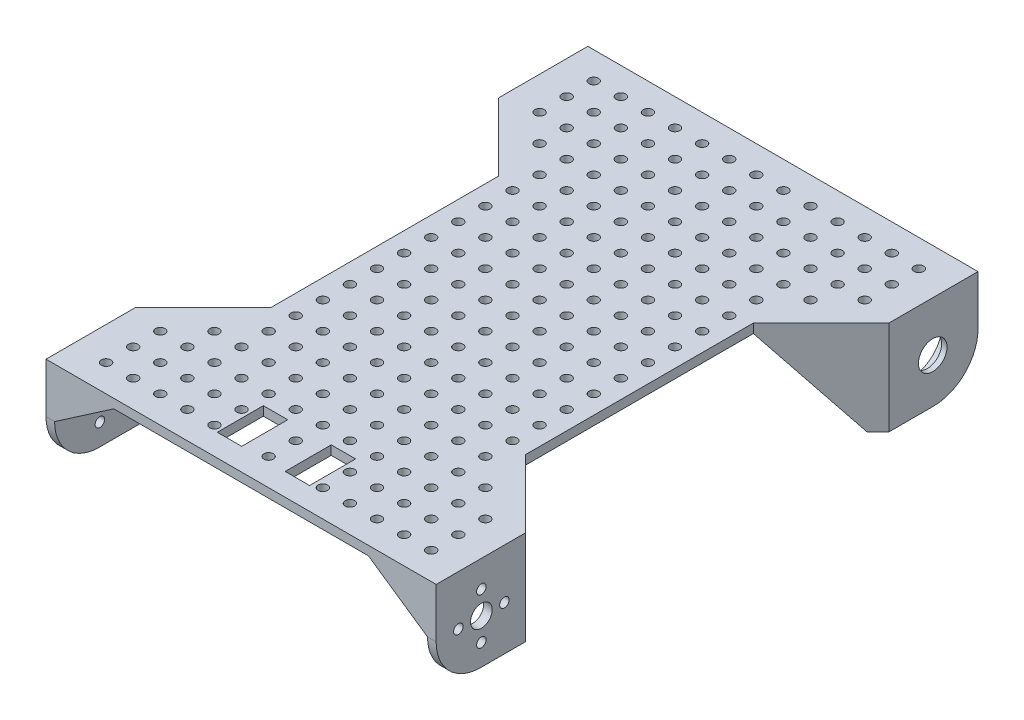
SolidWorks part; units mm, degrees
ref_plane "Alzado" through (0, 0, 0) normal (0, 0, 1) x (1, 0, 0)
ref_plane "Planta" through (0, 0, 0) normal (0, 1, 0) x (1, 0, 0)
ref_plane "Vista lateral" through (0, 0, 0) normal (1, 0, 0) x (0, 0, -1)
sketch "Croquis1" plane through (0, 0, 0) normal (1, 0, 0) x (0, 0, -1)
  line B0 (-67.1, 0) -> (67.1, 0)
  line B1 (-100, 0) -> (-100, 3.3682)
  line B2 (-100, 3.3682) -> (100, 3.3682)
  line B3 (-100, 0) -> (-100, -15)
  line B4 (-67.1, -15) -> (-70.1, -15) construction
  line B5 (-100, 0) -> (-67.1, 0) construction
  line B6 (-67.1, -15) -> (-67.1, 0)
  line B7 (0, 3.3682) -> (0, 0) construction
  line B8 (100, 0) -> (67.1, 0) construction
  line B9 (100, 0) -> (100, 3.3682)
  line B10 (100, 0) -> (67.1, 0) construction
  line B11 (100, 0) -> (100, -15)
  line B12 (67.1, -15) -> (67.1, 0)
  arc B13 (-100, -15) -> (-67.1, -15) centre (-83.55, -15) ccw
  circle B14 centre (-83.3, -15) radius 13.2 construction
  circle B15 centre (-83.3, -23.5) radius 1.75
  circle B16 centre (-91.8, -15) radius 1.75
  circle B17 centre (-74.8, -15) radius 1.75
  circle B18 centre (-83.3, -6.5) radius 1.75
  circle B19 centre (-83.3, -15) radius 4
  circle B20 centre (83.3, -15) radius 5.275
  arc B21 (100, -15) -> (67.1, -15) centre (83.55, -15) cw
sketch_block_instance "Bloque1-1"
sketch_block "Bloque1"
extrude "Saliente-Extruir1" add sketch "Croquis1" along normal blind 2
sketch "Croquis2" plane through (2, 0, 0) normal (1, 0, 0) x (0, 0, -1)
  line L0 (100, -15) -> (100, 3.3682) construction
  line L1 (-100, 3.3682) -> (100, 3.3682)
  line L2 (-100, 3.3682) -> (-100, 0)
  line L3 (-100, 0) -> (100, 0)
  line L4 (100, 3.3682) -> (100, 0)
extrude "Saliente-Extruir2" add sketch "Croquis2" along normal blind 70
sketch "Croquis3" plane through (0, 0, 0) normal (0, -1, 0) x (1, 0, 0)
  line L0 (0, 67.1) -> (25, 42.1)
  line L1 (25, 42.1) -> (25, -42.1)
  line L2 (25, -42.1) -> (0, -67.1)
  line L3 (0, -67.1) -> (0, 67.1)
  dimension "D1" = 25
  dimension "D2" = 25
  dimension "D3" = 25
extrude "Cortar-Extruir1" cut sketch "Croquis3" against normal through all
sketch "Croquis5" plane through (2, 0, 0) normal (1, 0, 0) x (0, 0, -1)
  line L3 (-67.1, 0) -> (-100, 0)
  line L4 (-100, 0) -> (-100, -15)
  line L5 (-67.1, -15) -> (-67.1, 0)
  line L6 (-67.1, 0) -> (-100, 0)
  line L7 (-100, 0) -> (-100, -15)
  line L8 (-67.1, -15) -> (-67.1, 0)
  circle A1 centre (-83.3, -23.5) radius 1.75
  circle A2 centre (-83.3, -23.5) radius 1.75
  circle A3 centre (-91.8, -15) radius 1.75
  circle A4 centre (-91.8, -15) radius 1.75
  circle A5 centre (-74.8, -15) radius 1.75
  circle A6 centre (-74.8, -15) radius 1.75
  circle A7 centre (-83.3, -6.5) radius 1.75
  circle A8 centre (-83.3, -6.5) radius 1.75
  circle A9 centre (-83.3, -15) radius 4
  circle A10 centre (-83.3, -15) radius 4
  arc A11 (-100, -15) -> (-67.1, -15) centre (-83.55, -15) ccw
  arc A12 (-100, -15) -> (-67.1, -15) centre (-83.55, -15) ccw
  dimension "D1" = 0
  dimension "D2" = 0
  dimension "D3" = 0
  dimension "D4" = 0
  dimension "D5" = 0
  dimension "D6" = 0
extrude "Saliente-Extruir3" add sketch "Croquis5" along normal blind 1.175
sketch "Croquis6" plane through (2, 0, 0) normal (1, 0, 0) x (0, 0, -1)
  line L3 (100, 0) -> (67.1, 0)
  line L4 (67.1, 0) -> (67.1, -15)
  line L5 (100, -15) -> (100, 0)
  line L6 (100, 0) -> (67.1, 0)
  line L7 (67.1, 0) -> (67.1, -15)
  line L8 (100, -15) -> (100, 0)
  circle A0 centre (83.55, -15) radius 11.25
  arc A1 (67.1, -15) -> (100, -15) centre (83.55, -15) ccw
  arc A2 (67.1, -15) -> (100, -15) centre (83.55, -15) ccw
  dimension "D2" = 22.5
  dimension "D1" = 0
extrude "Saliente-Extruir4" add sketch "Croquis6" along normal blind 6.05
sketch "Croquis8" plane through (3.175, 0, 0) normal (1, 0, 0) x (0, 0, -1)
  line L0 (-83.55, -31.45) -> (-67.1, -31.45)
  line L1 (-67.1, -31.45) -> (-67.1, -15)
  line L2 (83.55, -31.45) -> (67.1, -31.45)
  line L3 (-67.1, -15) -> (-67.1, 0)
  line L4 (-67.1, 0) -> (-100, 0)
  line L5 (-100, 0) -> (-100, -15)
  line L9 (67.1, -31.45) -> (67.1, -15)
  arc A0 (67.1, -15) -> (100, -15) centre (83.55, -15) ccw construction
  arc A1 (-100, -15) -> (-67.1, -15) centre (-83.55, -15) ccw
  arc A2 (-83.55, -31.45) -> (-67.1, -15) centre (-83.55, -15) ccw
  arc A3 (67.1, -15) -> (83.55, -31.45) centre (83.55, -15) ccw
  dimension "D1" = 0
extrude "Saliente-Extruir5" add sketch "Croquis8" against normal up to surface (3.175 mm away) up to face at (0, -15, 79.3)
sketch "Croquis10" plane through (3.175, 0, 0) normal (1, 0, 0) x (0, 0, -1)
  line L2 (67.1, -15) -> (67.1, -31.45)
  line L3 (67.1, -31.45) -> (83.55, -31.45)
  line L4 (67.1, -15) -> (67.1, -31.45)
  line L5 (67.1, -31.45) -> (83.55, -31.45)
  arc A1 (67.1, -15) -> (83.55, -31.45) centre (83.55, -15) ccw
  arc A2 (67.1, -15) -> (83.55, -31.45) centre (83.55, -15) ccw
  dimension "D1" = 0
extrude "Saliente-Extruir6" add sketch "Croquis10" along normal up to surface (4.875 mm away) up to face at (8.05, -11.6125, -83.55)
sketch "Croquis9" plane through (0, 0, 0) normal (0, -1, 0) x (1, 0, 0)
  line L0 (0, 67.1) -> (25, 42.1)
  line L1 (25, 42.1) -> (25, 45.275)
  line L2 (25, 45.275) -> (3.175, 67.1)
  line L3 (0, -67.1) -> (25, -42.1)
  line L4 (25, -42.1) -> (25, -50.15)
  line L5 (25, -50.15) -> (8.05, -67.1)
  line L6 (8.05, -100) -> (8.05, -67.1) construction
  line L7 (8.05, -67.1) -> (0, -67.1)
  line M3 (0, -67.1) -> (8.05, -67.1)
  line M9 (3.175, 67.1) -> (0, 67.1)
  line M10 (0, 67.1) -> (25, 42.1)
  line M12 (25, -42.1) -> (0, -67.1)
extrude "Saliente-Extruir7" add sketch "Croquis9" along normal up to surface (31.45 mm away) contours L1 L2 M9 M10 | L5 L4 M12 M3 up to face at (1.5875, -31.45, 75.325)
sketch "Croquis11" plane through (37.575, 0, -37.575) normal (0.7071, 0, -0.7071) x (-0.7071, 0, -0.7071)
  line L0 (41.7547, -31.45) -> (12.0915, 0)
  line L1 (12.0915, 0) -> (12.0915, -31.45)
  line L2 (12.0915, -31.45) -> (41.7547, -31.45)
extrude "Cortar-Extruir2" cut sketch "Croquis11" against normal through all
sketch "Croquis12" plane through (35.1375, 0, 35.1375) normal (0.7071, 0, 0.7071) x (0.7071, 0, -0.7071)
  line L0 (-45.2018, -31.45) -> (-12.0915, 0)
  line L1 (-12.0915, 0) -> (-12.0915, -31.45)
  line L2 (-12.0915, -31.45) -> (-45.2018, -31.45)
extrude "Cortar-Extruir3" cut sketch "Croquis12" against normal through all
sketch "Croquis13" plane through (3.175, 0, 0) normal (1, 0, 0) x (0, 0, -1)
  line L0 (-100, 0) -> (-100, -15) construction
  line L1 (-100, 0) -> (-97, 0)
  line L2 (-100, 0) -> (-100, -15)
  line L3 (-100, -15) -> (-97, -15)
  line L4 (-97, 0) -> (-97, -15)
  line L5 (100, 0) -> (97, 0)
  line L6 (100, 0) -> (100, -15)
  line L7 (100, -15) -> (97, -15)
  line L8 (97, 0) -> (97, -15)
  line L9 (100, -15) -> (100, 0) construction
  dimension "D1" = 3
  dimension "D2" = 3
extrude "Saliente-Extruir8" add sketch "Croquis13" along normal up to surface (21.825 mm away) up to face at (25, 1.6841, 0)
sketch "Croquis14" plane through (0, 0, 100) normal (0, 0, 1) x (1, 0, 0)
  line L0 (3.175, -15) -> (25, 0)
  line L1 (25, 0) -> (25, -15)
  line L2 (25, -15) -> (3.175, -15)
extrude "Cortar-Extruir4" cut sketch "Croquis14" against normal up to surface (3 mm away) up to face at (14.0875, -7.5, 97)
sketch "Croquis15" plane through (0, 0, -100) normal (0, 0, -1) x (-1, 0, 0)
  line L0 (-8.05, -15) -> (-25, 0)
  line L1 (-25, 0) -> (-25, -15)
  line L2 (-25, -15) -> (-8.05, -15)
extrude "Cortar-Extruir5" cut sketch "Croquis15" against normal up to surface (3 mm away) up to face at (16.525, -7.5, -97)
ref_plane "Plano1" through (72, 0, 0) normal (1, 0, 0) x (0, 0, -1)
mirror "Simetría1" about plane through (72, 0, 0) normal (1, 0, 0) of bodies 113
sketch "Croquis16" plane through (0, 0, 0) normal (0, -1, 0) x (1, 0, 0)
  line L0 (3.175, 97) -> (3.175, -97) construction
  line L1 (25, -97) -> (8.05, -97) construction
  line L2 (119, 100) -> (25, 100) construction
  line L3 (72, 100) -> (72, -100) construction
  line L4 (119, 100) -> (25, 100) construction
  line L5 (119, -100) -> (25, -100) construction
  circle A0 centre (12.175, 90) radius 1.75
  circle A1 centre (22.175, 90) radius 1.75
  circle A2 centre (32.175, 90) radius 1.75
  circle A3 centre (42.175, 90) radius 1.75
  circle A4 centre (52.175, 90) radius 1.75
  circle A5 centre (62.175, 90) radius 1.75
  circle A6 centre (72.175, 90) radius 1.75
  circle A7 centre (82.175, 90) radius 1.75
  circle A8 centre (92.175, 90) radius 1.75
  circle A9 centre (102.175, 90) radius 1.75
  circle A10 centre (112.175, 90) radius 1.75
  circle A11 centre (122.175, 90) radius 1.75
  circle A12 centre (132.175, 90) radius 1.75
  circle A13 centre (22.175, 80) radius 1.75
  circle A14 centre (32.175, 80) radius 1.75
  circle A15 centre (42.175, 80) radius 1.75
  circle A16 centre (52.175, 80) radius 1.75
  circle A17 centre (62.175, 80) radius 1.75
  circle A18 centre (72.175, 80) radius 1.75
  circle A19 centre (82.175, 80) radius 1.75
  circle A20 centre (92.175, 80) radius 1.75
  circle A21 centre (102.175, 80) radius 1.75
  circle A22 centre (112.175, 80) radius 1.75
  circle A23 centre (122.175, 80) radius 1.75
  circle A24 centre (132.175, 80) radius 1.75
  circle A25 centre (22.175, 70) radius 1.75
  circle A26 centre (32.175, 70) radius 1.75
  circle A27 centre (42.175, 70) radius 1.75
  circle A28 centre (52.175, 70) radius 1.75
  circle A29 centre (62.175, 70) radius 1.75
  circle A30 centre (72.175, 70) radius 1.75
  circle A31 centre (82.175, 70) radius 1.75
  circle A32 centre (92.175, 70) radius 1.75
  circle A33 centre (102.175, 70) radius 1.75
  circle A34 centre (112.175, 70) radius 1.75
  circle A35 centre (122.175, 70) radius 1.75
  circle A36 centre (132.175, 70) radius 1.75
  circle A37 centre (22.175, 60) radius 1.75
  circle A38 centre (32.175, 60) radius 1.75
  circle A39 centre (42.175, 60) radius 1.75
  circle A40 centre (52.175, 60) radius 1.75
  circle A41 centre (62.175, 60) radius 1.75
  circle A42 centre (72.175, 60) radius 1.75
  circle A43 centre (82.175, 60) radius 1.75
  circle A44 centre (92.175, 60) radius 1.75
  circle A45 centre (102.175, 60) radius 1.75
  circle A46 centre (112.175, 60) radius 1.75
  circle A47 centre (122.175, 60) radius 1.75
  circle A50 centre (32.175, 50) radius 1.75
  circle A51 centre (42.175, 50) radius 1.75
  circle A52 centre (52.175, 50) radius 1.75
  circle A53 centre (62.175, 50) radius 1.75
  circle A54 centre (72.175, 50) radius 1.75
  circle A55 centre (82.175, 50) radius 1.75
  circle A56 centre (92.175, 50) radius 1.75
  circle A57 centre (102.175, 50) radius 1.75
  circle A58 centre (112.175, 50) radius 1.75
  circle A62 centre (32.175, 40) radius 1.75
  circle A63 centre (42.175, 40) radius 1.75
  circle A64 centre (52.175, 40) radius 1.75
  circle A65 centre (62.175, 40) radius 1.75
  circle A66 centre (72.175, 40) radius 1.75
  circle A67 centre (82.175, 40) radius 1.75
  circle A68 centre (92.175, 40) radius 1.75
  circle A69 centre (102.175, 40) radius 1.75
  circle A70 centre (112.175, 40) radius 1.75
  circle A74 centre (32.175, 30) radius 1.75
  circle A75 centre (42.175, 30) radius 1.75
  circle A76 centre (52.175, 30) radius 1.75
  circle A77 centre (62.175, 30) radius 1.75
  circle A78 centre (72.175, 30) radius 1.75
  circle A79 centre (82.175, 30) radius 1.75
  circle A80 centre (92.175, 30) radius 1.75
  circle A81 centre (102.175, 30) radius 1.75
  circle A82 centre (112.175, 30) radius 1.75
  circle A86 centre (32.175, 20) radius 1.75
  circle A87 centre (42.175, 20) radius 1.75
  circle A88 centre (52.175, 20) radius 1.75
  circle A89 centre (62.175, 20) radius 1.75
  circle A90 centre (72.175, 20) radius 1.75
  circle A91 centre (82.175, 20) radius 1.75
  circle A92 centre (92.175, 20) radius 1.75
  circle A93 centre (102.175, 20) radius 1.75
  circle A94 centre (112.175, 20) radius 1.75
  circle A98 centre (32.175, 10) radius 1.75
  circle A99 centre (42.175, 10) radius 1.75
  circle A100 centre (52.175, 10) radius 1.75
  circle A101 centre (62.175, 10) radius 1.75
  circle A102 centre (72.175, 10) radius 1.75
  circle A103 centre (82.175, 10) radius 1.75
  circle A104 centre (92.175, 10) radius 1.75
  circle A105 centre (102.175, 10) radius 1.75
  circle A106 centre (112.175, 10) radius 1.75
  circle A110 centre (32.175, 0) radius 1.75
  circle A111 centre (42.175, 0) radius 1.75
  circle A112 centre (52.175, 0) radius 1.75
  circle A113 centre (62.175, 0) radius 1.75
  circle A114 centre (72.175, 0) radius 1.75
  circle A115 centre (82.175, 0) radius 1.75
  circle A116 centre (92.175, 0) radius 1.75
  circle A117 centre (102.175, 0) radius 1.75
  circle A118 centre (112.175, 0) radius 1.75
  circle A122 centre (32.175, -10) radius 1.75
  circle A123 centre (42.175, -10) radius 1.75
  circle A124 centre (52.175, -10) radius 1.75
  circle A125 centre (62.175, -10) radius 1.75
  circle A126 centre (72.175, -10) radius 1.75
  circle A127 centre (82.175, -10) radius 1.75
  circle A128 centre (92.175, -10) radius 1.75
  circle A129 centre (102.175, -10) radius 1.75
  circle A130 centre (112.175, -10) radius 1.75
  circle A134 centre (32.175, -20) radius 1.75
  circle A135 centre (42.175, -20) radius 1.75
  circle A136 centre (52.175, -20) radius 1.75
  circle A137 centre (62.175, -20) radius 1.75
  circle A138 centre (72.175, -20) radius 1.75
  circle A139 centre (82.175, -20) radius 1.75
  circle A140 centre (92.175, -20) radius 1.75
  circle A141 centre (102.175, -20) radius 1.75
  circle A142 centre (112.175, -20) radius 1.75
  circle A146 centre (32.175, -30) radius 1.75
  circle A147 centre (42.175, -30) radius 1.75
  circle A148 centre (52.175, -30) radius 1.75
  circle A149 centre (62.175, -30) radius 1.75
  circle A150 centre (72.175, -30) radius 1.75
  circle A151 centre (82.175, -30) radius 1.75
  circle A152 centre (92.175, -30) radius 1.75
  circle A153 centre (102.175, -30) radius 1.75
  circle A154 centre (112.175, -30) radius 1.75
  circle A158 centre (32.175, -40) radius 1.75
  circle A159 centre (42.175, -40) radius 1.75
  circle A160 centre (52.175, -40) radius 1.75
  circle A161 centre (62.175, -40) radius 1.75
  circle A162 centre (72.175, -40) radius 1.75
  circle A163 centre (82.175, -40) radius 1.75
  circle A164 centre (92.175, -40) radius 1.75
  circle A165 centre (102.175, -40) radius 1.75
  circle A166 centre (112.175, -40) radius 1.75
  circle A170 centre (32.175, -50) radius 1.75
  circle A171 centre (42.175, -50) radius 1.75
  circle A172 centre (52.175, -50) radius 1.75
  circle A173 centre (62.175, -50) radius 1.75
  circle A174 centre (72.175, -50) radius 1.75
  circle A175 centre (82.175, -50) radius 1.75
  circle A176 centre (92.175, -50) radius 1.75
  circle A177 centre (102.175, -50) radius 1.75
  circle A178 centre (112.175, -50) radius 1.75
  circle A181 centre (22.175, -60) radius 1.75
  circle A182 centre (32.175, -60) radius 1.75
  circle A183 centre (42.175, -60) radius 1.75
  circle A184 centre (52.175, -60) radius 1.75
  circle A185 centre (62.175, -60) radius 1.75
  circle A186 centre (72.175, -60) radius 1.75
  circle A187 centre (82.175, -60) radius 1.75
  circle A188 centre (92.175, -60) radius 1.75
  circle A189 centre (102.175, -60) radius 1.75
  circle A190 centre (112.175, -60) radius 1.75
  circle A191 centre (122.175, -60) radius 1.75
  circle A193 centre (22.175, -70) radius 1.75
  circle A194 centre (32.175, -70) radius 1.75
  circle A195 centre (42.175, -70) radius 1.75
  circle A196 centre (52.175, -70) radius 1.75
  circle A197 centre (62.175, -70) radius 1.75
  circle A198 centre (72.175, -70) radius 1.75
  circle A199 centre (82.175, -70) radius 1.75
  circle A200 centre (92.175, -70) radius 1.75
  circle A201 centre (102.175, -70) radius 1.75
  circle A202 centre (112.175, -70) radius 1.75
  circle A203 centre (122.175, -70) radius 1.75
  circle A204 centre (132.175, -70) radius 1.75
  circle A205 centre (22.175, -80) radius 1.75
  circle A206 centre (32.175, -80) radius 1.75
  circle A207 centre (42.175, -80) radius 1.75
  circle A208 centre (52.175, -80) radius 1.75
  circle A209 centre (62.175, -80) radius 1.75
  circle A210 centre (72.175, -80) radius 1.75
  circle A211 centre (82.175, -80) radius 1.75
  circle A212 centre (92.175, -80) radius 1.75
  circle A213 centre (102.175, -80) radius 1.75
  circle A214 centre (112.175, -80) radius 1.75
  circle A215 centre (122.175, -80) radius 1.75
  circle A216 centre (132.175, -80) radius 1.75
  circle A217 centre (22.175, -90) radius 1.75
  circle A218 centre (32.175, -90) radius 1.75
  circle A219 centre (42.175, -90) radius 1.75
  circle A220 centre (52.175, -90) radius 1.75
  circle A221 centre (62.175, -90) radius 1.75
  circle A222 centre (72.175, -90) radius 1.75
  circle A223 centre (82.175, -90) radius 1.75
  circle A224 centre (92.175, -90) radius 1.75
  circle A225 centre (102.175, -90) radius 1.75
  circle A226 centre (112.175, -90) radius 1.75
  circle A227 centre (122.175, -90) radius 1.75
  circle A228 centre (132.175, -90) radius 1.75
  circle A229 centre (12.175, 80) radius 1.75
  circle A230 centre (12.175, 70) radius 1.75
  circle A244 centre (12.175, -70) radius 1.75
  circle A245 centre (12.175, -80) radius 1.75
  circle A246 centre (12.175, -90) radius 1.75
  circle A247 centre (22.175, 40) radius 1.75 [skipped]
  circle A248 centre (12.175, 60) radius 1.75 [skipped]
  circle A249 centre (22.175, 50) radius 1.75 [skipped]
  circle A250 centre (22.175, 30) radius 1.75 [skipped]
  circle A251 centre (22.175, 20) radius 1.75 [skipped]
  circle A252 centre (22.175, 10) radius 1.75 [skipped]
  circle A253 centre (22.175, 0) radius 1.75 [skipped]
  circle A254 centre (22.175, -10) radius 1.75 [skipped]
  circle A255 centre (22.175, -20) radius 1.75 [skipped]
  circle A256 centre (22.175, -30) radius 1.75 [skipped]
  circle A257 centre (22.175, -40) radius 1.75 [skipped]
  circle A258 centre (22.175, -50) radius 1.75 [skipped]
  circle A259 centre (12.175, 50) radius 1.75 [skipped]
  circle A260 centre (12.175, 40) radius 1.75 [skipped]
  circle A261 centre (12.175, 30) radius 1.75 [skipped]
  circle A262 centre (12.175, 20) radius 1.75 [skipped]
  circle A263 centre (12.175, 10) radius 1.75 [skipped]
  circle A264 centre (12.175, 0) radius 1.75 [skipped]
  circle A265 centre (12.175, -10) radius 1.75 [skipped]
  circle A266 centre (12.175, -20) radius 1.75 [skipped]
  circle A267 centre (12.175, -30) radius 1.75 [skipped]
  circle A268 centre (12.175, -40) radius 1.75 [skipped]
  circle A269 centre (12.175, -50) radius 1.75 [skipped]
  circle A270 centre (12.175, -60) radius 1.75 [skipped]
  circle A271 centre (122.175, 50) radius 1.75 [skipped]
  circle A272 centre (132.175, 50) radius 1.75 [skipped]
  circle A273 centre (122.175, 40) radius 1.75 [skipped]
  circle A274 centre (132.175, 40) radius 1.75 [skipped]
  circle A275 centre (122.175, 30) radius 1.75 [skipped]
  circle A276 centre (132.175, 30) radius 1.75 [skipped]
  circle A277 centre (122.175, 20) radius 1.75 [skipped]
  circle A278 centre (132.175, 20) radius 1.75 [skipped]
  circle A279 centre (122.175, 10) radius 1.75 [skipped]
  circle A280 centre (132.175, 10) radius 1.75 [skipped]
  circle A281 centre (122.175, 0) radius 1.75 [skipped]
  circle A282 centre (132.175, 0) radius 1.75 [skipped]
  circle A283 centre (122.175, -10) radius 1.75 [skipped]
  circle A284 centre (132.175, -10) radius 1.75 [skipped]
  circle A285 centre (122.175, -20) radius 1.75 [skipped]
  circle A286 centre (132.175, -20) radius 1.75 [skipped]
  circle A287 centre (122.175, -30) radius 1.75 [skipped]
  circle A288 centre (132.175, -30) radius 1.75 [skipped]
  circle A289 centre (122.175, -40) radius 1.75 [skipped]
  circle A290 centre (132.175, -40) radius 1.75 [skipped]
  circle A291 centre (122.175, -50) radius 1.75 [skipped]
  circle A292 centre (132.175, -50) radius 1.75 [skipped]
  circle A293 centre (132.175, 60) radius 1.75 [skipped]
  circle A294 centre (132.175, -60) radius 1.75 [skipped]
  dimension "D1" = 3.5
  dimension "D2" = 9
  dimension "D3" = 10
  dimension "D6" = 10
  dimension "D7" = 10
  dimension "D4" = 13
  dimension "D5" = 19
extrude "Cortar-Extruir6" cut sketch "Croquis16" against normal through all
sketch "Croquis18" plane through (0, 3.3682, 0) normal (0, 1, 0) x (1, 0, 0)
  line L0 (3.175, -67.1) -> (3.175, -97) construction
  line L1 (54.975, -74.75) -> (63.975, -74.75)
  line L2 (54.975, -74.75) -> (54.975, -91.75)
  line L3 (54.975, -91.75) -> (63.975, -91.75)
  line L4 (63.975, -74.75) -> (63.975, -91.75)
  line L6 (72, -100) -> (72, 100) construction
  line L7 (144, -100) -> (0, -100) construction
  line L8 (144, 100) -> (0, 100) construction
  line L9 (80.025, -74.75) -> (80.025, -91.75)
  line L10 (89.025, -91.75) -> (80.025, -91.75)
  line L11 (89.025, -74.75) -> (89.025, -91.75)
  line L12 (89.025, -74.75) -> (80.025, -74.75)
  circle A0 centre (62.175, -90) radius 1.75 construction
  dimension "D1" = 51.8
  dimension "D2" = 17
  dimension "D3" = 9
extrude "Cortar-Extruir7" cut sketch "Croquis18" against normal through all
